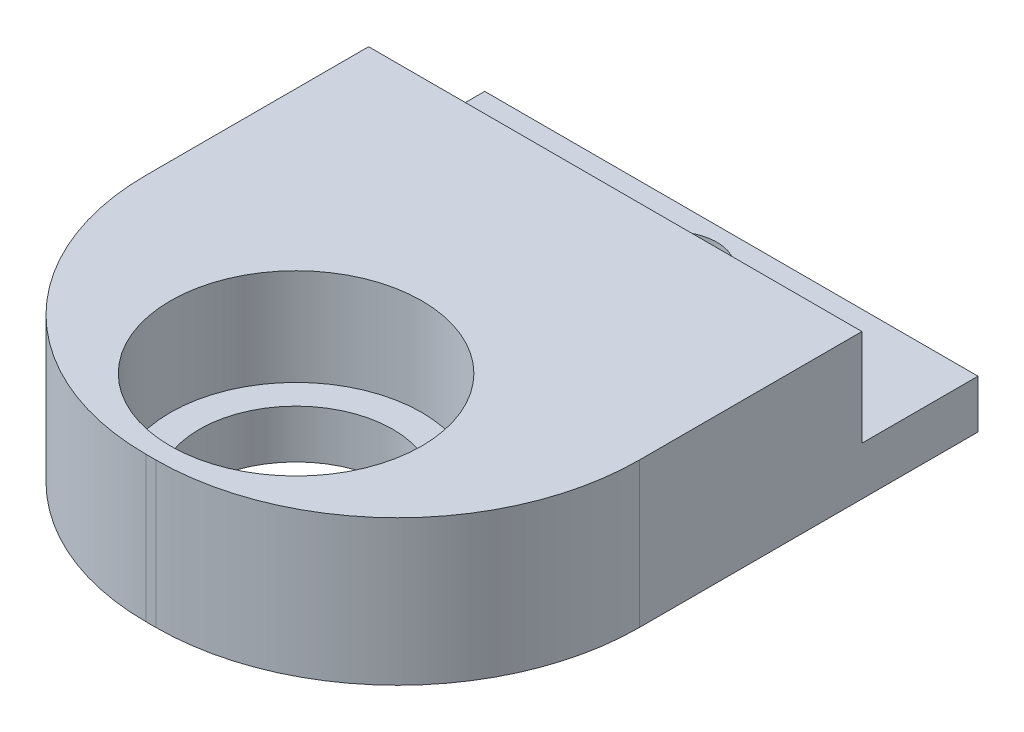
SolidWorks part; units mm, degrees
ref_plane "Płaszczyzna przednia" through (0, 0, 0) normal (0, 0, 1) x (1, 0, 0)
ref_plane "Płaszczyzna górna" through (0, 0, 0) normal (0, 1, 0) x (1, 0, 0)
ref_plane "Płaszczyzna prawa" through (0, 0, 0) normal (1, 0, 0) x (0, 0, -1)
sketch "Szkic1" plane through (0, 0, 0) normal (0, 1, 0) x (1, 0, 0)
  line L1 (25.5, -30) -> (-25.5, -30)
  line L2 (25.5, -30) -> (25.5, 30)
  line L3 (25.5, 30) -> (-25.5, 30)
  line L4 (-25.5, -30) -> (-25.5, 30)
  line L5 (25.5, -30) -> (-25.5, 30) construction
  line L6 (25.5, 30) -> (-25.5, -30) construction
  circle A0 centre (0, 24) radius 4.5
  circle A1 centre (0, -15) radius 10
  point P0 (0, 0)
  dimension "D3" = 9
  dimension "D4" = 20
  dimension "D1" = 51
  dimension "D2" = 6
  dimension "D5" = 15
  dimension "D6" = 60
extrude "Dodanie-wyciągnięcie1" add sketch "Szkic1" along normal blind 5
sketch "Szkic2" plane through (0, 0, 0) normal (0, 1, 0) x (1, 0, 0)
  line L0 (-25.5, 18) -> (25.5, 18)
  line L1 (-25.5, 30) -> (-25.5, -30) construction
  line L2 (25.5, -30) -> (25.5, 30) construction
  line L3 (25.5, 18) -> (25.5, -30)
  line L4 (25.5, -30) -> (-25.5, -30)
  line L5 (-25.5, -30) -> (-25.5, 18)
  line L6 (25.5, 30) -> (-25.5, 30) construction
  circle A0 centre (0, -15) radius 13
  dimension "D2" = 26
  dimension "D1" = 12
extrude "Dodanie-wyciągnięcie2" add sketch "Szkic2" along normal blind 10 from surface at 5 starting at face at (0, 5, -19.5)
fillet "Zaokrąglenie1" radius 25 2 edges at (25.5, 7.5, 30) (-25.5, 7.5, 30)
